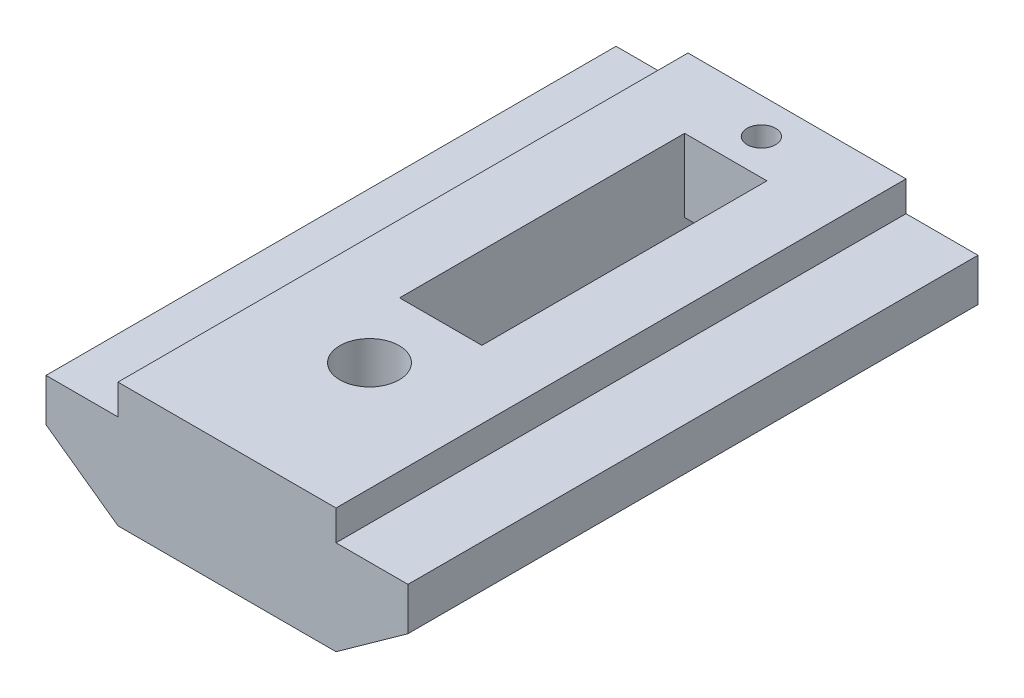
SolidWorks part; units mm, degrees
ref_plane "Front Plane" through (0, 0, 0) normal (0, 0, 1) x (1, 0, 0)
ref_plane "Top Plane" through (0, 0, 0) normal (0, 1, 0) x (1, 0, 0)
ref_plane "Right Plane" through (0, 0, 0) normal (1, 0, 0) x (0, 0, -1)
sketch "Sketch1" plane through (0, 0, 0) normal (0, 0, 1) x (1, 0, 0)
  line L0 (0, 0) -> (0, 13004.4718) construction
  line L1 (-7.65, 5.1167) -> (7.65, 5.1167)
  line L2 (7.65, 5.1167) -> (7.65, 3)
  line L3 (7.65, 0) -> (12.7, 0) construction
  line L4 (12.7, 0) -> (12.7, 3)
  line L5 (12.7, 3) -> (7.65, 3)
  line L6 (7.65, 0) -> (7.65, -3.62) construction
  line L7 (7.65, -3.62) -> (-7.65, -3.62)
  line L8 (-7.65, 0) -> (-7.65, -3.62) construction
  line L9 (-12.7, 0) -> (-12.7, 3)
  line L10 (-12.7, 3) -> (-7.65, 3)
  line L11 (-7.65, 0) -> (-12.7, 0) construction
  line L12 (-7.65, 5.1167) -> (-7.65, 3)
  line L13 (0, 0) -> (50000, 0) construction
  line L14 (-12.7, 0) -> (-7.65, -3.62)
  line L15 (7.65, -3.62) -> (12.7, 0)
  point P12 (0, -3.62)
  point P17 (0, 5.1167)
  dimension "D1" = 2.1167
  dimension "D2" = 25.4
  dimension "D3" = 15.3
  dimension "D4" = 3.62
  dimension "D5" = 3
extrude "Boss-Extrude1" add sketch "Sketch1" along normal blind 40
sketch "Sketch2" plane through (0, -3.62, 0) normal (0, -1, 0) x (1, 0, 0)
  line L0 (-7.65, 40) -> (7.65, 40) construction
  line L1 (-5.6485, 40) -> (5.6485, 40) construction
  line L2 (-5.6485, 40) -> (-5.6485, 20) construction
  line L3 (-5.6485, 20) -> (5.6485, 20) construction
  line L4 (5.6485, 40) -> (5.6485, 20) construction
  line L5 (-5.6485, 40) -> (5.6485, 20) construction
  line L6 (-5.6485, 20) -> (5.6485, 40) construction
  line L7 (0, 0) -> (0, 50000) construction
  line L8 (-7.65, 0) -> (7.65, 0) construction
  circle A0 centre (0, 30) radius 2.0828
  circle A1 centre (0, 2.5) radius 1
  point P0 (0, 30)
  point P11 (0, 0)
  dimension "D3" = 4.1656
  dimension "D4" = 2
  dimension "D1" = 20
  dimension "D2" = 11.2969
  dimension "D5" = 2.5
extrude "Cut-Extrude1" cut sketch "Sketch2" against normal through all
sketch "Sketch3" plane through (0, -3.62, 0) normal (0, -1, 0) x (1, 0, 0)
  line L0 (0, 0) -> (0, 50000) construction
  line L1 (-7.65, 0) -> (7.65, 0) construction
  line L3 (-2.8883, 25) -> (2.8883, 25)
  line L4 (-2.8883, 25) -> (-2.8883, 5)
  line L5 (-2.8883, 5) -> (2.8883, 5)
  line L6 (2.8883, 25) -> (2.8883, 5)
  line L7 (-2.8883, 25) -> (2.8883, 5) construction
  line L8 (-2.8883, 5) -> (2.8883, 25) construction
  point P4 (0, 0)
  point P5 (0, 15)
  dimension "D1" = 20
  dimension "D2" = 5
extrude "Cut-Extrude2" cut sketch "Sketch3" against normal through all
sketch "Sketch4" plane through (0, -3.62, 0) normal (0, -1, 0) x (1, 0, 0)
  line L1 (-2.8883, 0) -> (2.8883, 0)
  line L2 (-2.8883, 0) -> (-2.8883, 5)
  line L3 (-2.8883, 5) -> (2.8883, 5)
  line L4 (2.8883, 0) -> (2.8883, 5)
  line L5 (-2.8883, 0) -> (2.8883, 5) construction
  line L6 (-2.8883, 5) -> (2.8883, 0) construction
  point P0 (0, 2.5)
extrude "Cut-Extrude3" cut sketch "Sketch4" against normal blind 3.62
sketch "Sketch5" plane through (0, -3.62, 0) normal (0, -1, 0) x (1, 0, 0)
  circle A0 centre (0, 30) radius 4.0005
  dimension "D1" = 8.001
extrude "Cut-Extrude4" cut sketch "Sketch5" against normal blind 2.2098
